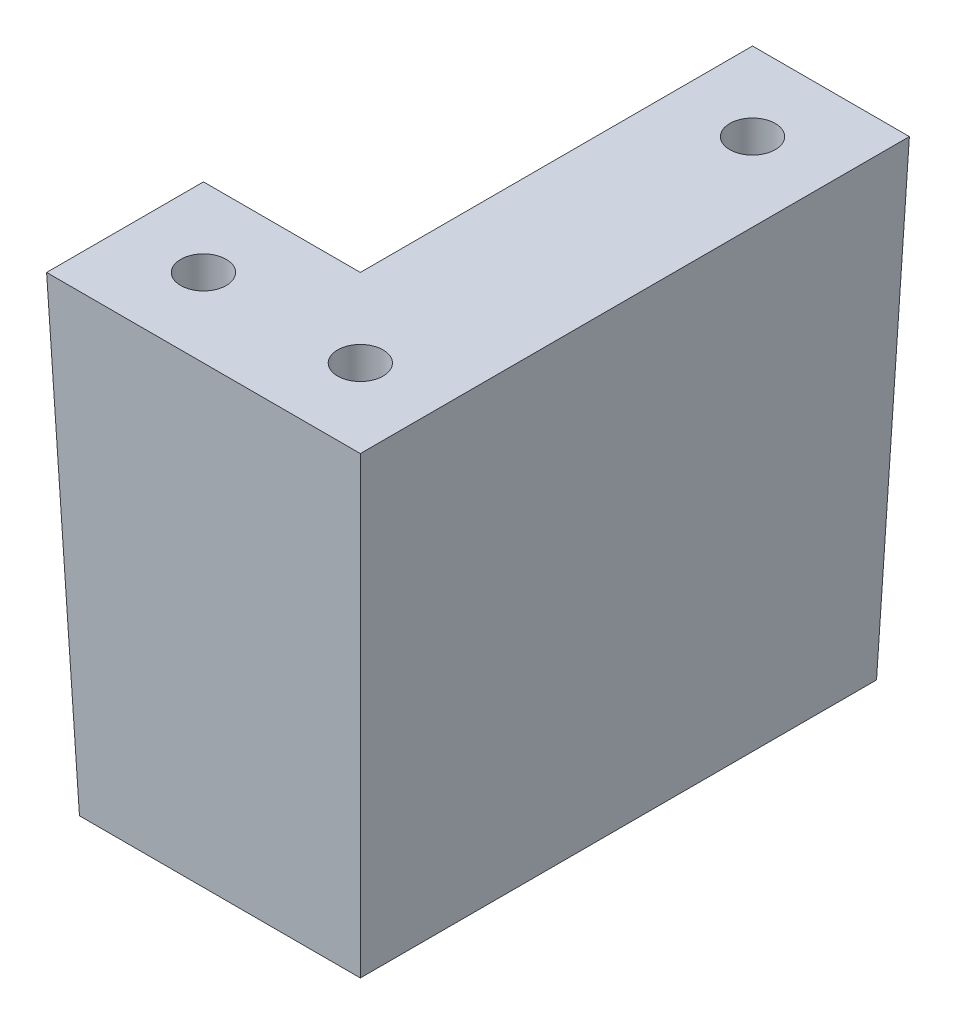
SolidWorks part; units mm, degrees
ref_plane "Front Plane" through (0, 0, 0) normal (0, 0, 1) x (1, 0, 0)
ref_plane "Top Plane" through (0, 0, 0) normal (0, 1, 0) x (1, 0, 0)
ref_plane "Right Plane" through (0, 0, 0) normal (1, 0, 0) x (0, 0, -1)
sketch "Sketch1" plane through (0, 0, 0) normal (0, 1, 0) x (1, 0, 0)
  line L0 (-1000, 10) -> (49000, 10) construction
  line L1 (0, 0) -> (40, 0)
  line L2 (0, 0) -> (0, 20)
  line L3 (20, 70) -> (40, 70)
  line L4 (40, 0) -> (40, 70)
  line L7 (0, 20) -> (20, 20)
  line L8 (20, 70) -> (20, 20)
  line L9 (30, -930) -> (30, 49070) construction
  point P10 (0, 10)
  point P13 (30, 70)
  dimension "D1" = 20
  dimension "D2" = 20
  dimension "D3" = 70
  dimension "D4" = 40
extrude "Boss-Extrude1" add sketch "Sketch1" against normal blind 60 draft 2
hole_wizard "CBORE for M5 SBHCS1" positions "Sketch2" profile "Sketch3" counterbore size "M5" standard "ANSI Metric" end condition through all
sketch "Sketch2" plane through (0, -60, 0) normal (0, -1, 0) x (-1, 0, 0)
  line L0 (201000, 10) -> (-249000, 10) construction
  line L1 (-30, -200930) -> (-30, 249070) construction
  line L2 (0, 0) -> (0, 20) construction
  line L3 (-20, 70) -> (-40, 70) construction
  point P0 (-10, 10)
  point P4 (-30, 10)
  point P8 (-30, 60)
  dimension "D1" = 10
  dimension "D2" = 10
sketch "Sketch3" plane through (10, -60, -10) normal (1, 0, 0) x (0, 0, -1)
  line L0 (0, 0) -> (0, 60)
  line L1 (0, 60) -> (2.9, 60)
  line L3 (2.9, 60) -> (2.9, 55)
  line L4 (2.9, 55) -> (5.75, 55)
  line L5 (5.75, 55) -> (5.75, 0)
  line L7 (5.75, 0) -> (0, 0)
  line L11 (0, -6.35) -> (0, 107.95) construction
  dimension "Thru Hole Dia." = 5.8
  dimension "Thru Hole Depth" = 60
  dimension "C'Bore Dia." = 11.5
  dimension "C'Bore Depth" = 55
